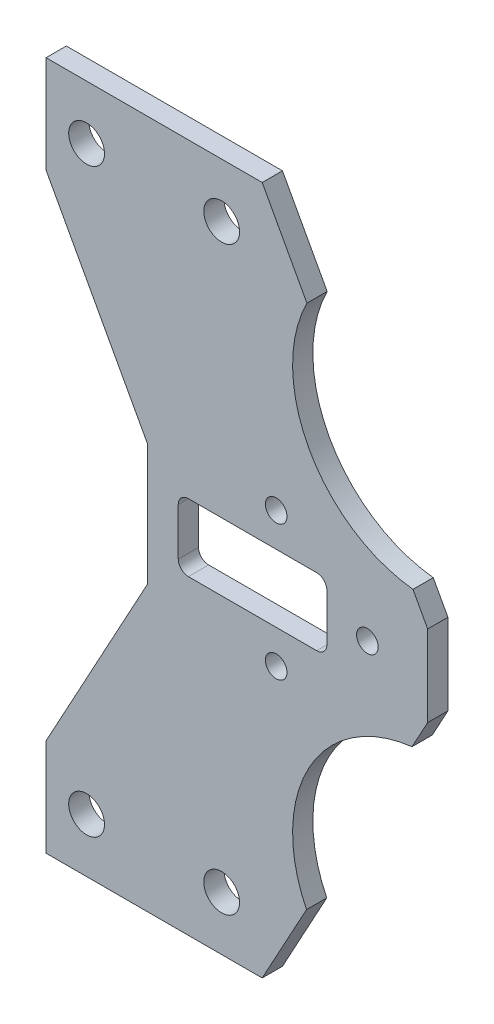
SolidWorks part; units mm, degrees
material "Thornel Mat VMA"
ref_plane "Front Plane" through (0, 0, 0) normal (0, 0, 1) x (1, 0, 0)
ref_plane "Top Plane" through (0, 0, 0) normal (0, 1, 0) x (1, 0, 0)
ref_plane "Right Plane" through (0, 0, 0) normal (1, 0, 0) x (0, 0, -1)
sketch "Sketch1" plane through (0, 0, 0) normal (0, 0, 1) x (1, 0, 0)
  line L0 (-34, 52.265) -> (-34, 37.8445)
  line L1 (-34, -49.74) -> (-2, -49.74)
  line L2 (-2, -49.74) -> (22.5011, -4.7375)
  line L3 (29.3339, -4.7375) -> (15.6683, -4.7375) construction
  line L4 (22.5011, -4.7375) -> (22.5011, 7.2625)
  line L5 (15.6683, 7.2625) -> (29.3339, 7.2625) construction
  line L6 (22.5011, 7.2625) -> (-2, 52.265)
  line L7 (-2, 52.265) -> (-34, 52.265)
  line L8 (-34, 37.8445) -> (-19, 10.2933)
  line L9 (-19, 10.2933) -> (-19, -7.7683)
  line L10 (-19, -7.7683) -> (-34, -35.3195)
  line L11 (-34, -35.3195) -> (-34, -49.74)
  line L12 (6.0711, 6.2625) -> (-12.9289, 6.2625) construction
  line L13 (-14.4289, 4.7625) -> (-14.4289, -2.2375) construction
  line L14 (-12.9289, -3.7375) -> (6.0711, -3.7375) construction
  line L15 (7.5711, -2.2375) -> (7.5711, 4.7625) construction
  line L16 (7.5711, -2.2375) -> (7.5711, 4.7625)
  line L17 (-12.9289, -3.7375) -> (6.0711, -3.7375)
  line L18 (-14.4289, 4.7625) -> (-14.4289, -2.2375)
  line L19 (6.0711, 6.2625) -> (-12.9289, 6.2625)
  circle A0 centre (-28, 44.265) radius 2.65
  circle A1 centre (-8, 44.2629) radius 2.65
  circle A2 centre (-28, -41.7379) radius 2.65
  circle A3 centre (-8, -41.74) radius 2.65
  circle A4 centre (0.0711, 11.2625) radius 1.6
  circle A5 centre (13.5711, 1.2625) radius 1.6
  circle A6 centre (0.0711, -8.7375) radius 1.6
  arc A7 (-12.9289, 6.2625) -> (-14.4289, 4.7625) centre (-12.9289, 4.7625) ccw construction
  arc A8 (-14.4289, -2.2375) -> (-12.9289, -3.7375) centre (-12.9289, -2.2375) ccw construction
  arc A9 (6.0711, -3.7375) -> (7.5711, -2.2375) centre (6.0711, -2.2375) ccw construction
  arc A10 (7.5711, 4.7625) -> (6.0711, 6.2625) centre (6.0711, 4.7625) ccw construction
  arc A11 (7.5711, 4.7625) -> (6.0711, 6.2625) centre (6.0711, 4.7625) ccw
  arc A12 (6.0711, -3.7375) -> (7.5711, -2.2375) centre (6.0711, -2.2375) ccw
  arc A13 (-14.4289, -2.2375) -> (-12.9289, -3.7375) centre (-12.9289, -2.2375) ccw
  arc A14 (-12.9289, 6.2625) -> (-14.4289, 4.7625) centre (-12.9289, 4.7625) ccw
  dimension "D4" = 5.3
  dimension "D5" = 3.2
  dimension "D1" = 15
  dimension "D2" = 35
  dimension "D3" = 35
extrude "Extrude1" add sketch "Sketch1" along normal blind 3
sketch "Sketch2" plane through (0, 0, 3) normal (0, 0, 1) x (1, 0, 0)
  circle A0 centre (22.5011, 31.14) radius 20
  circle A1 centre (22.5011, -28.86) radius 20
  dimension "D1" = 40
extrude "Cut-Extrude1" cut sketch "Sketch2" against normal blind 3
